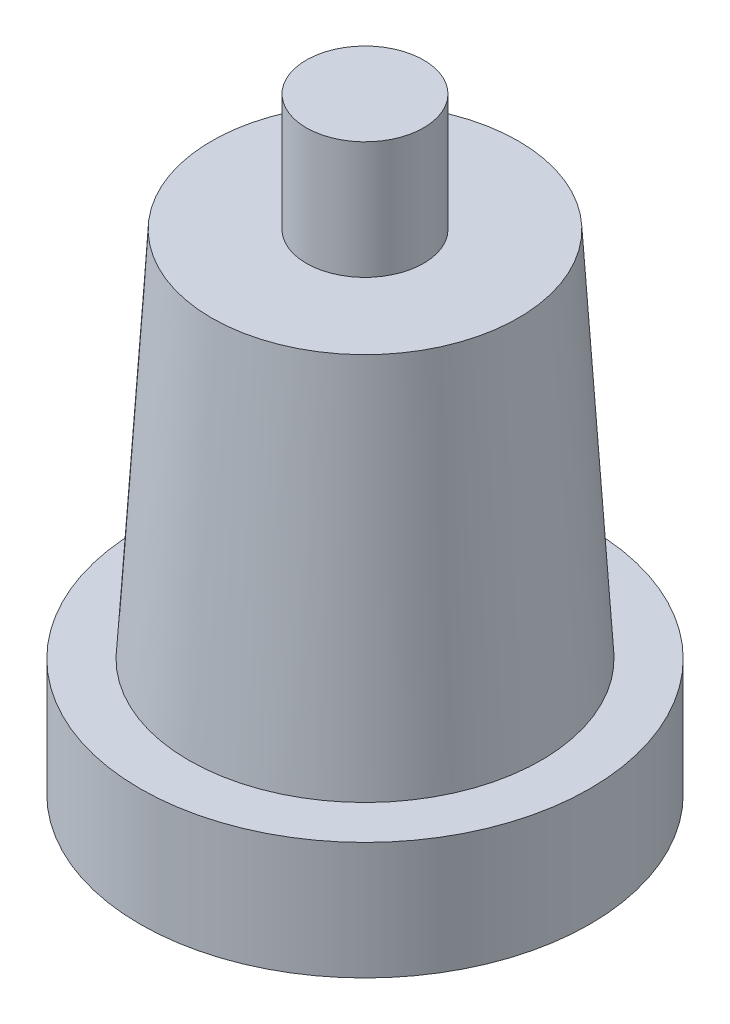
SolidWorks part; units mm, degrees
material "1023 Carbon Steel Sheet (SS)"
ref_plane "Front Plane" through (0, 0, 0) normal (0, 0, 1) x (1, 0, 0)
ref_plane "Top Plane" through (0, 0, 0) normal (0, 1, 0) x (1, 0, 0)
ref_plane "Right Plane" through (0, 0, 0) normal (1, 0, 0) x (0, 0, -1)
sketch "Sketch1" plane through (0, 0, 0) normal (0, 1, 0) x (1, 0, 0)
  circle A0 centre (0, 0) radius 115
extrude "Boss-Extrude1" add sketch "Sketch1" along normal blind 60
sketch "Sketch2" plane through (0, 60, 0) normal (0, 1, 0) x (1, 0, 0)
  circle A0 centre (0, 0) radius 90
extrude "Boss-Extrude2" add sketch "Sketch2" along normal blind 190 draft 3.5
sketch "Sketch3" plane through (0, 250, 0) normal (0, 1, 0) x (1, 0, 0)
  circle A0 centre (0, 0) radius 30
extrude "Boss-Extrude3" add sketch "Sketch3" along normal blind 60
